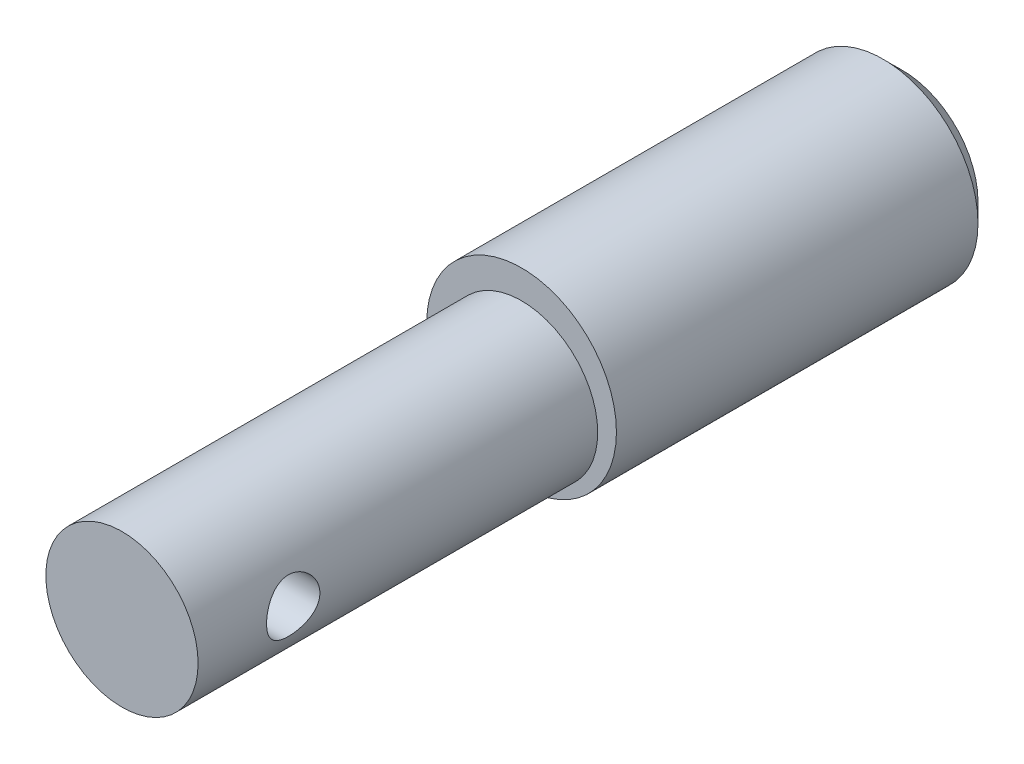
SolidWorks part; units mm, degrees
ref_plane "Front" through (0, 0, 0) normal (0, 0, 1) x (1, 0, 0)
ref_plane "Top" through (0, 0, 0) normal (0, 1, 0) x (1, 0, 0)
ref_plane "Right" through (0, 0, 0) normal (1, 0, 0) x (0, 0, -1)
sketch "Sketch1" plane through (0, 0, 0) normal (0, 0, 1) x (1, 0, 0)
  circle A0 centre (0, 0) radius 3.956
  dimension "D1" = 7.9121
extrude "Base-Extrude" add sketch "Sketch1" along normal mid plane 32.5437
chamfer "Chamfer1" distance 0.7937 angle 45 1 edges at (3.956, 0, -16.2719)
sketch "Silhouette" plane through (0, 0, 0) normal (1, 0, 0) x (0, 0, -1)
  line L1 (-16.2719, 2.7686) -> (0.3969, 2.7686)
  line L2 (-13.5156, -0.4064) -> (-0.4661, -0.4064) construction
  line L3 (-16.2719, 2.7686) -> (-16.2719, 3.9561)
  line L4 (50, 0) -> (-50, 0) construction
  line L5 (0.3969, 3.956) -> (-16.2719, 3.9561)
  line L6 (0.3969, 3.956) -> (0.3969, 2.7686)
  line L7 (-16.2719, 3.956) -> (-16.2719, -3.956) construction
  line L9 (16.2719, -3.1623) -> (16.2719, 3.1623) construction
  dimension "D1" = 0.4064
  dimension "D2" = 6.35
  dimension "D3" = 15.875
revolve "Cut-Revolve1" cut sketch "Silhouette" angle 360 about L2
sketch "Sketch5" plane through (0, 0, 0) normal (1, 0, 0) x (0, 0, -1)
  line L1 (-16.2719, 3.956) -> (-16.2719, -3.956) construction
  line L2 (0.3969, -0.4064) -> (-16.2719, -0.4064) construction
  circle A0 centre (-12.3031, -0.4064) radius 1.1122
  dimension "D1" = 2.2243
  dimension "D2" = 3.9688
extrude "Locking pin hole" cut sketch "Sketch5" against normal through all and the other way through all
